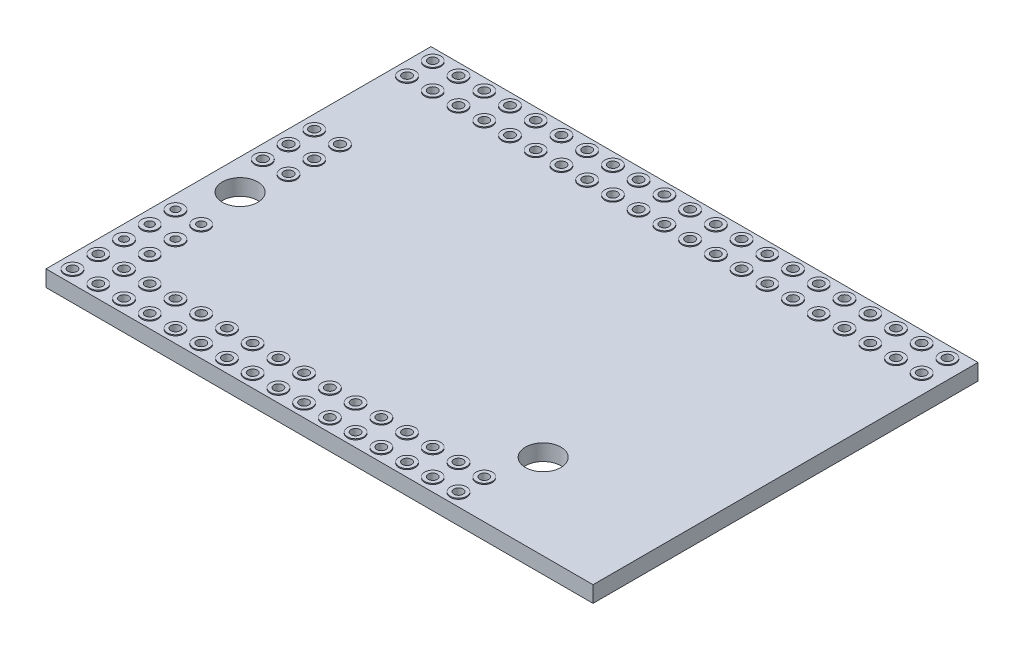
SolidWorks part; units mm, degrees
ref_plane "Front Plane" through (0, 0, 0) normal (0, 0, 1) x (1, 0, 0)
ref_plane "Top Plane" through (0, 0, 0) normal (0, 1, 0) x (1, 0, 0)
ref_plane "Right Plane" through (0, 0, 0) normal (1, 0, 0) x (0, 0, -1)
sketch "Sketch1" plane through (0, 0, 0) normal (0, 1, 0) x (1, 0, 0)
  line L1 (-27, 19) -> (27, 19)
  line L2 (-27, 19) -> (-27, -19)
  line L3 (-27, -19) -> (27, -19)
  line L4 (27, 19) -> (27, -19)
  line L5 (-27, 19) -> (27, -19) construction
  line L6 (-27, -19) -> (27, 19) construction
  point P0 (0, 0)
  dimension "D1" = 38
  dimension "D2" = 54
extrude "Boss-Extrude1" add sketch "Sketch1" along normal blind 1.6
sketch "Sketch2" plane through (0, 1.6, 0) normal (0, 1, 0) x (1, 0, 0)
  line L0 (-29.1683, 17.78) -> (28.2527, 17.78) construction
  line L1 (-33.9704, -17.78) -> (29.2072, -17.78) construction
  line L2 (-25.6, 21.7043) -> (-25.6, -25.273) construction
  circle A0 centre (-25.6, -17.78) radius 1 construction
  circle A1 centre (-25.6, -17.78) radius 0.45
  circle A2 centre (-23.06, -17.78) radius 0.45
  circle A3 centre (-20.52, -17.78) radius 0.45
  circle A4 centre (-17.98, -17.78) radius 0.45
  circle A5 centre (-15.44, -17.78) radius 0.45
  circle A6 centre (-12.9, -17.78) radius 0.45
  circle A7 centre (-10.36, -17.78) radius 0.45
  circle A8 centre (-7.82, -17.78) radius 0.45
  circle A9 centre (-5.28, -17.78) radius 0.45
  circle A10 centre (-2.74, -17.78) radius 0.45
  circle A11 centre (-0.2, -17.78) radius 0.45
  circle A12 centre (2.34, -17.78) radius 0.45
  circle A13 centre (4.88, -17.78) radius 0.45
  circle A14 centre (7.42, -17.78) radius 0.45
  circle A15 centre (9.96, -17.78) radius 0.45
  circle A16 centre (12.5, -17.78) radius 0.45
  circle A17 centre (-23.06, -15.24) radius 0.45
  circle A18 centre (-20.52, -15.24) radius 0.45
  circle A19 centre (-17.98, -15.24) radius 0.45
  circle A20 centre (-15.44, -15.24) radius 0.45
  circle A21 centre (-12.9, -15.24) radius 0.45
  circle A22 centre (-10.36, -15.24) radius 0.45
  circle A23 centre (-7.82, -15.24) radius 0.45
  circle A24 centre (-5.28, -15.24) radius 0.45
  circle A25 centre (-2.74, -15.24) radius 0.45
  circle A26 centre (-0.2, -15.24) radius 0.45
  circle A27 centre (2.34, -15.24) radius 0.45
  circle A28 centre (4.88, -15.24) radius 0.45
  circle A29 centre (7.42, -15.24) radius 0.45
  circle A30 centre (9.96, -15.24) radius 0.45
  circle A31 centre (12.5, -15.24) radius 0.45
  circle A32 centre (-25.6, -15.24) radius 0.45
  circle A33 centre (-25.6, 17.78) radius 0.45
  circle A34 centre (-23.06, 17.78) radius 0.45
  circle A35 centre (-20.52, 17.78) radius 0.45
  circle A36 centre (-17.98, 17.78) radius 0.45
  circle A37 centre (-15.44, 17.78) radius 0.45
  circle A38 centre (-12.9, 17.78) radius 0.45
  circle A39 centre (-10.36, 17.78) radius 0.45
  circle A40 centre (-7.82, 17.78) radius 0.45
  circle A41 centre (-5.28, 17.78) radius 0.45
  circle A42 centre (-2.74, 17.78) radius 0.45
  circle A43 centre (-0.2, 17.78) radius 0.45
  circle A44 centre (2.34, 17.78) radius 0.45
  circle A45 centre (4.88, 17.78) radius 0.45
  circle A46 centre (7.42, 17.78) radius 0.45
  circle A47 centre (9.96, 17.78) radius 0.45
  circle A48 centre (12.5, 17.78) radius 0.45
  circle A49 centre (15.04, 17.78) radius 0.45
  circle A50 centre (17.58, 17.78) radius 0.45
  circle A51 centre (20.12, 17.78) radius 0.45
  circle A52 centre (22.66, 17.78) radius 0.45
  circle A53 centre (25.2, 17.78) radius 0.45
  circle A54 centre (-23.06, 15.24) radius 0.45
  circle A55 centre (-20.52, 15.24) radius 0.45
  circle A56 centre (-17.98, 15.24) radius 0.45
  circle A57 centre (-15.44, 15.24) radius 0.45
  circle A58 centre (-12.9, 15.24) radius 0.45
  circle A59 centre (-10.36, 15.24) radius 0.45
  circle A60 centre (-7.82, 15.24) radius 0.45
  circle A61 centre (-5.28, 15.24) radius 0.45
  circle A62 centre (-2.74, 15.24) radius 0.45
  circle A63 centre (-0.2, 15.24) radius 0.45
  circle A64 centre (2.34, 15.24) radius 0.45
  circle A65 centre (4.88, 15.24) radius 0.45
  circle A66 centre (7.42, 15.24) radius 0.45
  circle A67 centre (9.96, 15.24) radius 0.45
  circle A68 centre (12.5, 15.24) radius 0.45
  circle A69 centre (15.04, 15.24) radius 0.45
  circle A70 centre (17.58, 15.24) radius 0.45
  circle A71 centre (20.12, 15.24) radius 0.45
  circle A72 centre (22.66, 15.24) radius 0.45
  circle A73 centre (25.2, 15.24) radius 0.45
  circle A74 centre (-25.6, 15.24) radius 0.45
  circle A75 centre (-25.6, -12.7) radius 0.3945
  circle A76 centre (-23.06, -12.7) radius 0.3945
  circle A77 centre (-23.06, -10.16) radius 0.3945
  circle A78 centre (-23.06, -7.62) radius 0.3945
  circle A79 centre (-25.6, -10.16) radius 0.3945
  circle A80 centre (-25.6, -7.62) radius 0.3945
  circle A81 centre (-25.6, 1) radius 0.464
  circle A82 centre (-23.06, 1) radius 0.464
  circle A83 centre (-23.06, 3.54) radius 0.464
  circle A84 centre (-23.06, 6.08) radius 0.464
  circle A85 centre (-25.6, 3.54) radius 0.464
  circle A86 centre (-25.6, 6.08) radius 0.464
  dimension "D4" = 2
  dimension "D5" = 0.9
  dimension "D8" = 0.9
  dimension "D1" = 17.78
  dimension "D2" = 35.56
  dimension "D3" = 25.6
  dimension "D11" = 2.54
  dimension "D14" = 8.62
  dimension "D6" = 16
  dimension "D7" = 2
  dimension "D9" = 21
  dimension "D10" = 2
  dimension "D12" = 2
  dimension "D13" = 3
  dimension "D15" = 2
  dimension "D16" = 3
extrude "Cut-Extrude1" cut sketch "Sketch2" against normal through all
sketch "Sketch3" plane through (0, 1.6, 0) normal (0, 1, 0) x (1, 0, 0)
  circle A0 centre (-23.984, -2.8562) radius 1.75
  circle A1 centre (13.6469, -10.5718) radius 1.75
  dimension "D1" = 3.5
extrude "Cut-Extrude2" cut sketch "Sketch3" against normal through all
sketch "Sketch4" plane through (0, 1.6, 0) normal (0, 1, 0) x (1, 0, 0)
  circle A0 centre (-25.6, 17.78) radius 0.8
  circle A1 centre (-23.06, 17.78) radius 0.8
  circle A2 centre (-20.52, 17.78) radius 0.8
  circle A3 centre (-17.98, 17.78) radius 0.8
  circle A4 centre (-15.44, 17.78) radius 0.8
  circle A5 centre (-12.9, 17.78) radius 0.8
  circle A6 centre (-10.36, 17.78) radius 0.8
  circle A7 centre (-7.82, 17.78) radius 0.8
  circle A8 centre (-5.28, 17.78) radius 0.8
  circle A9 centre (-2.74, 17.78) radius 0.8
  circle A10 centre (-0.2, 17.78) radius 0.8
  circle A11 centre (2.34, 17.78) radius 0.8
  circle A12 centre (4.88, 17.78) radius 0.8
  circle A13 centre (7.42, 17.78) radius 0.8
  circle A14 centre (9.96, 17.78) radius 0.8
  circle A15 centre (12.5, 17.78) radius 0.8
  circle A16 centre (15.04, 17.78) radius 0.8
  circle A17 centre (17.58, 17.78) radius 0.8
  circle A18 centre (20.12, 17.78) radius 0.8
  circle A19 centre (22.66, 17.78) radius 0.8
  circle A20 centre (25.2, 17.78) radius 0.8
  circle A21 centre (-23.06, 15.24) radius 0.8
  circle A22 centre (-20.52, 15.24) radius 0.8
  circle A23 centre (-17.98, 15.24) radius 0.8
  circle A24 centre (-15.44, 15.24) radius 0.8
  circle A25 centre (-12.9, 15.24) radius 0.8
  circle A26 centre (-10.36, 15.24) radius 0.8
  circle A27 centre (-7.82, 15.24) radius 0.8
  circle A28 centre (-5.28, 15.24) radius 0.8
  circle A29 centre (-2.74, 15.24) radius 0.8
  circle A30 centre (-0.2, 15.24) radius 0.8
  circle A31 centre (2.34, 15.24) radius 0.8
  circle A32 centre (4.88, 15.24) radius 0.8
  circle A33 centre (7.42, 15.24) radius 0.8
  circle A34 centre (9.96, 15.24) radius 0.8
  circle A35 centre (12.5, 15.24) radius 0.8
  circle A36 centre (15.04, 15.24) radius 0.8
  circle A37 centre (17.58, 15.24) radius 0.8
  circle A38 centre (20.12, 15.24) radius 0.8
  circle A39 centre (22.66, 15.24) radius 0.8
  circle A40 centre (25.2, 15.24) radius 0.8
  circle A41 centre (-25.6, 15.24) radius 0.8
  circle A42 centre (-25.6, -17.78) radius 0.8
  circle A43 centre (-23.06, -17.78) radius 0.8
  circle A44 centre (-20.52, -17.78) radius 0.8
  circle A45 centre (-17.98, -17.78) radius 0.8
  circle A46 centre (-15.44, -17.78) radius 0.8
  circle A47 centre (-12.9, -17.78) radius 0.8
  circle A48 centre (-10.36, -17.78) radius 0.8
  circle A49 centre (-7.82, -17.78) radius 0.8
  circle A50 centre (-5.28, -17.78) radius 0.8
  circle A51 centre (-2.74, -17.78) radius 0.8
  circle A52 centre (-0.2, -17.78) radius 0.8
  circle A53 centre (2.34, -17.78) radius 0.8
  circle A54 centre (4.88, -17.78) radius 0.8
  circle A55 centre (7.42, -17.78) radius 0.8
  circle A56 centre (9.96, -17.78) radius 0.8
  circle A57 centre (12.5, -17.78) radius 0.8
  circle A58 centre (-23.06, -15.24) radius 0.8
  circle A59 centre (-20.52, -15.24) radius 0.8
  circle A60 centre (-17.98, -15.24) radius 0.8
  circle A61 centre (-15.44, -15.24) radius 0.8
  circle A62 centre (-12.9, -15.24) radius 0.8
  circle A63 centre (-10.36, -15.24) radius 0.8
  circle A64 centre (-7.82, -15.24) radius 0.8
  circle A65 centre (-5.28, -15.24) radius 0.8
  circle A66 centre (-2.74, -15.24) radius 0.8
  circle A67 centre (-0.2, -15.24) radius 0.8
  circle A68 centre (2.34, -15.24) radius 0.8
  circle A69 centre (4.88, -15.24) radius 0.8
  circle A70 centre (7.42, -15.24) radius 0.8
  circle A71 centre (9.96, -15.24) radius 0.8
  circle A72 centre (12.5, -15.24) radius 0.8
  circle A73 centre (-25.6, -15.24) radius 0.8
  circle A74 centre (-25.6, 6.08) radius 0.8
  circle A75 centre (-25.6, -7.62) radius 0.8
  circle A76 centre (-23.06, 6.08) radius 0.8
  circle A77 centre (-23.06, -7.62) radius 0.8
  circle A78 centre (-23.06, 3.54) radius 0.8
  circle A79 centre (-23.06, -10.16) radius 0.8
  circle A80 centre (-23.06, 1) radius 0.8
  circle A81 centre (-23.06, -12.7) radius 0.8
  circle A82 centre (-25.6, 3.54) radius 0.8
  circle A83 centre (-25.6, -10.16) radius 0.8
  circle A84 centre (-25.6, 1) radius 0.8
  circle A85 centre (-25.6, -12.7) radius 0.8
  circle A86 centre (-23.06, 6.08) radius 0.464 construction
  circle A87 centre (-23.06, 3.54) radius 0.464 construction
  circle A88 centre (-23.06, 1) radius 0.464 construction
  circle A89 centre (-25.6, 1) radius 0.464 construction
  circle A90 centre (-25.6, 3.54) radius 0.464 construction
  circle A91 centre (-25.6, 6.08) radius 0.464 construction
  circle A92 centre (-23.06, 6.08) radius 0.464
  circle A93 centre (-23.06, 3.54) radius 0.464
  circle A94 centre (-23.06, 1) radius 0.464
  circle A95 centre (-25.6, 1) radius 0.464
  circle A96 centre (-25.6, 3.54) radius 0.464
  circle A97 centre (-25.6, 6.08) radius 0.464
  circle A98 centre (-25.6, 17.78) radius 0.45 construction
  circle A99 centre (-25.6, 15.24) radius 0.45 construction
  circle A100 centre (-23.06, 17.78) radius 0.45 construction
  circle A101 centre (-20.52, 17.78) radius 0.45 construction
  circle A102 centre (-20.52, 15.24) radius 0.45 construction
  circle A103 centre (-23.06, 15.24) radius 0.45 construction
  circle A104 centre (-17.98, 17.78) radius 0.45 construction
  circle A105 centre (-17.98, 15.24) radius 0.45 construction
  circle A106 centre (-15.44, 17.78) radius 0.45 construction
  circle A107 centre (-15.44, 15.24) radius 0.45 construction
  circle A108 centre (-12.9, 15.24) radius 0.45 construction
  circle A109 centre (-12.9, 17.78) radius 0.45 construction
  circle A110 centre (-10.36, 17.78) radius 0.45 construction
  circle A111 centre (-10.36, 15.24) radius 0.45 construction
  circle A112 centre (-7.82, 17.78) radius 0.45 construction
  circle A113 centre (-7.82, 15.24) radius 0.45 construction
  circle A114 centre (-25.6, 17.78) radius 0.45
  circle A115 centre (-25.6, 15.24) radius 0.45
  circle A116 centre (-23.06, 17.78) radius 0.45
  circle A117 centre (-20.52, 17.78) radius 0.45
  circle A118 centre (-20.52, 15.24) radius 0.45
  circle A119 centre (-23.06, 15.24) radius 0.45
  circle A120 centre (-17.98, 17.78) radius 0.45
  circle A121 centre (-17.98, 15.24) radius 0.45
  circle A122 centre (-15.44, 17.78) radius 0.45
  circle A123 centre (-15.44, 15.24) radius 0.45
  circle A124 centre (-12.9, 15.24) radius 0.45
  circle A125 centre (-12.9, 17.78) radius 0.45
  circle A126 centre (-10.36, 17.78) radius 0.45
  circle A127 centre (-10.36, 15.24) radius 0.45
  circle A128 centre (-7.82, 17.78) radius 0.45
  circle A129 centre (-7.82, 15.24) radius 0.45
  circle A130 centre (-5.28, 17.78) radius 0.45 construction
  circle A131 centre (-5.28, 15.24) radius 0.45 construction
  circle A132 centre (-2.74, 17.78) radius 0.45 construction
  circle A133 centre (-0.2, 17.78) radius 0.45 construction
  circle A134 centre (2.34, 17.78) radius 0.45 construction
  circle A135 centre (4.88, 17.78) radius 0.45 construction
  circle A136 centre (7.42, 17.78) radius 0.45 construction
  circle A137 centre (9.96, 17.78) radius 0.45 construction
  circle A138 centre (12.5, 17.78) radius 0.45 construction
  circle A139 centre (15.04, 17.78) radius 0.45 construction
  circle A140 centre (17.58, 17.78) radius 0.45 construction
  circle A141 centre (20.12, 17.78) radius 0.45 construction
  circle A142 centre (22.66, 17.78) radius 0.45 construction
  circle A143 centre (25.2, 17.78) radius 0.45 construction
  circle A144 centre (-5.28, 17.78) radius 0.45
  circle A145 centre (-5.28, 15.24) radius 0.45
  circle A146 centre (-2.74, 17.78) radius 0.45
  circle A147 centre (-0.2, 17.78) radius 0.45
  circle A148 centre (2.34, 17.78) radius 0.45
  circle A149 centre (4.88, 17.78) radius 0.45
  circle A150 centre (7.42, 17.78) radius 0.45
  circle A151 centre (9.96, 17.78) radius 0.45
  circle A152 centre (12.5, 17.78) radius 0.45
  circle A153 centre (15.04, 17.78) radius 0.45
  circle A154 centre (17.58, 17.78) radius 0.45
  circle A155 centre (20.12, 17.78) radius 0.45
  circle A156 centre (22.66, 17.78) radius 0.45
  circle A157 centre (25.2, 17.78) radius 0.45
  circle A158 centre (-2.74, 15.24) radius 0.45 construction
  circle A159 centre (-0.2, 15.24) radius 0.45 construction
  circle A160 centre (2.34, 15.24) radius 0.45 construction
  circle A161 centre (4.88, 15.24) radius 0.45 construction
  circle A162 centre (7.42, 15.24) radius 0.45 construction
  circle A163 centre (9.96, 15.24) radius 0.45 construction
  circle A164 centre (12.5, 15.24) radius 0.45 construction
  circle A165 centre (15.04, 15.24) radius 0.45 construction
  circle A166 centre (17.58, 15.24) radius 0.45 construction
  circle A167 centre (20.12, 15.24) radius 0.45 construction
  circle A168 centre (22.66, 15.24) radius 0.45 construction
  circle A169 centre (25.2, 15.24) radius 0.45 construction
  circle A170 centre (-2.74, 15.24) radius 0.45
  circle A171 centre (-0.2, 15.24) radius 0.45
  circle A172 centre (2.34, 15.24) radius 0.45
  circle A173 centre (4.88, 15.24) radius 0.45
  circle A174 centre (7.42, 15.24) radius 0.45
  circle A175 centre (9.96, 15.24) radius 0.45
  circle A176 centre (12.5, 15.24) radius 0.45
  circle A177 centre (15.04, 15.24) radius 0.45
  circle A178 centre (17.58, 15.24) radius 0.45
  circle A179 centre (20.12, 15.24) radius 0.45
  circle A180 centre (22.66, 15.24) radius 0.45
  circle A181 centre (25.2, 15.24) radius 0.45
  circle A182 centre (-25.6, -7.62) radius 0.3945 construction
  circle A183 centre (-25.6, -10.16) radius 0.3945 construction
  circle A184 centre (-25.6, -12.7) radius 0.3945 construction
  circle A185 centre (-25.6, -15.24) radius 0.45 construction
  circle A186 centre (-25.6, -17.78) radius 0.45 construction
  circle A187 centre (-23.06, -17.78) radius 0.45 construction
  circle A188 centre (-23.06, -15.24) radius 0.45 construction
  circle A189 centre (-23.06, -12.7) radius 0.3945 construction
  circle A190 centre (-23.06, -10.16) radius 0.3945 construction
  circle A191 centre (-23.06, -7.62) radius 0.3945 construction
  circle A192 centre (-25.6, -7.62) radius 0.3945
  circle A193 centre (-25.6, -10.16) radius 0.3945
  circle A194 centre (-25.6, -12.7) radius 0.3945
  circle A195 centre (-25.6, -15.24) radius 0.45
  circle A196 centre (-25.6, -17.78) radius 0.45
  circle A197 centre (-23.06, -17.78) radius 0.45
  circle A198 centre (-23.06, -15.24) radius 0.45
  circle A199 centre (-23.06, -12.7) radius 0.3945
  circle A200 centre (-23.06, -10.16) radius 0.3945
  circle A201 centre (-23.06, -7.62) radius 0.3945
  circle A202 centre (-20.52, -15.24) radius 0.45 construction
  circle A203 centre (-17.98, -15.24) radius 0.45 construction
  circle A204 centre (-15.44, -15.24) radius 0.45 construction
  circle A205 centre (-12.9, -15.24) radius 0.45 construction
  circle A206 centre (-10.36, -15.24) radius 0.45 construction
  circle A207 centre (-7.82, -15.24) radius 0.45 construction
  circle A208 centre (-5.28, -15.24) radius 0.45 construction
  circle A209 centre (-2.74, -15.24) radius 0.45 construction
  circle A210 centre (-0.2, -15.24) radius 0.45 construction
  circle A211 centre (2.34, -15.24) radius 0.45 construction
  circle A212 centre (2.34, -17.78) radius 0.45 construction
  circle A213 centre (-0.2, -17.78) radius 0.45 construction
  circle A214 centre (-2.74, -17.78) radius 0.45 construction
  circle A215 centre (-5.28, -17.78) radius 0.45 construction
  circle A216 centre (-7.82, -17.78) radius 0.45 construction
  circle A217 centre (-10.36, -17.78) radius 0.45 construction
  circle A218 centre (-12.9, -17.78) radius 0.45 construction
  circle A219 centre (-15.44, -17.78) radius 0.45 construction
  circle A220 centre (-17.98, -17.78) radius 0.45 construction
  circle A221 centre (-20.52, -17.78) radius 0.45 construction
  circle A222 centre (-20.52, -15.24) radius 0.45
  circle A223 centre (-17.98, -15.24) radius 0.45
  circle A224 centre (-15.44, -15.24) radius 0.45
  circle A225 centre (-12.9, -15.24) radius 0.45
  circle A226 centre (-10.36, -15.24) radius 0.45
  circle A227 centre (-7.82, -15.24) radius 0.45
  circle A228 centre (-5.28, -15.24) radius 0.45
  circle A229 centre (-2.74, -15.24) radius 0.45
  circle A230 centre (-0.2, -15.24) radius 0.45
  circle A231 centre (2.34, -15.24) radius 0.45
  circle A232 centre (2.34, -17.78) radius 0.45
  circle A233 centre (-0.2, -17.78) radius 0.45
  circle A234 centre (-2.74, -17.78) radius 0.45
  circle A235 centre (-5.28, -17.78) radius 0.45
  circle A236 centre (-7.82, -17.78) radius 0.45
  circle A237 centre (-10.36, -17.78) radius 0.45
  circle A238 centre (-12.9, -17.78) radius 0.45
  circle A239 centre (-15.44, -17.78) radius 0.45
  circle A240 centre (-17.98, -17.78) radius 0.45
  circle A241 centre (-20.52, -17.78) radius 0.45
  circle A242 centre (12.5, -15.24) radius 0.45 construction
  circle A243 centre (12.5, -17.78) radius 0.45 construction
  circle A244 centre (9.96, -17.78) radius 0.45 construction
  circle A245 centre (9.96, -15.24) radius 0.45 construction
  circle A246 centre (7.42, -15.24) radius 0.45 construction
  circle A247 centre (4.88, -15.24) radius 0.45 construction
  circle A248 centre (4.88, -17.78) radius 0.45 construction
  circle A249 centre (7.42, -17.78) radius 0.45 construction
  circle A250 centre (12.5, -15.24) radius 0.45
  circle A251 centre (12.5, -17.78) radius 0.45
  circle A252 centre (9.96, -17.78) radius 0.45
  circle A253 centre (9.96, -15.24) radius 0.45
  circle A254 centre (7.42, -15.24) radius 0.45
  circle A255 centre (4.88, -15.24) radius 0.45
  circle A256 centre (4.88, -17.78) radius 0.45
  circle A257 centre (7.42, -17.78) radius 0.45
  dimension "D1" = 1.6
  dimension "D2" = 21
  dimension "D3" = 2
  dimension "D4" = 16
  dimension "D5" = 2
  dimension "D6" = 2
  dimension "D7" = 3
extrude "Boss-Extrude2" add sketch "Sketch4" along normal blind 0.1 and the other way offset from surface (1.7 mm away) 0.1 other way up to face at (13.6469, 0, 12.3218)
